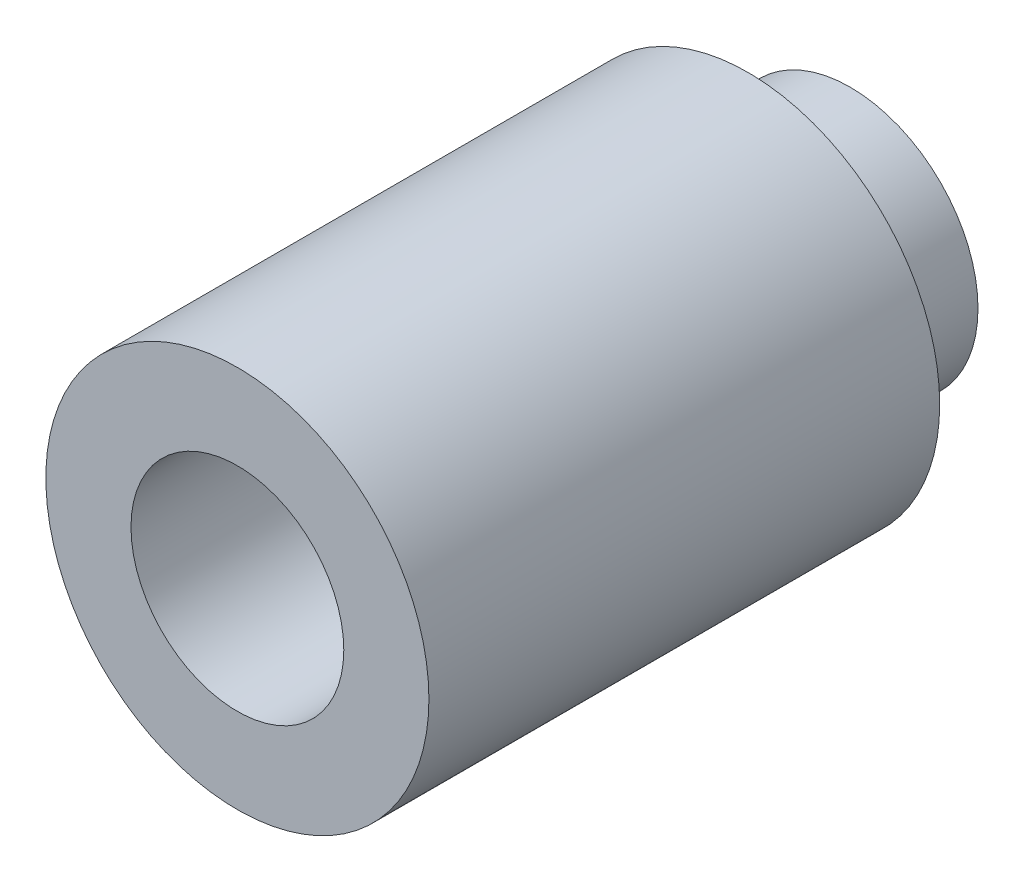
SolidWorks part; units mm, degrees
ref_plane "前视基准面" through (0, 0, 0) normal (0, 0, 1) x (1, 0, 0)
ref_plane "上视基准面" through (0, 0, 0) normal (0, 1, 0) x (1, 0, 0)
ref_plane "右视基准面" through (0, 0, 0) normal (1, 0, 0) x (0, 0, -1)
other "Configuration Table"
sketch "草图1" plane through (0, 0, 0) normal (0, 0, 1) x (1, 0, 0)
  circle A0 centre (0, 0) radius 1.25
  circle A1 centre (0, 0) radius 2.25
  dimension "D1" = 2.5
  dimension "D2" = 4.5
extrude "凸台-拉伸1" add sketch "草图1" along normal blind 6
sketch "草图2" plane through (0, 0, 0) normal (0, 0, -1) x (-1, 0, 0)
  circle A0 centre (0, 0) radius 1.5
  circle A1 centre (0, 0) radius 1.25 construction
  circle A2 centre (0, 0) radius 1.25
  dimension "D1" = 3
extrude "凸台-拉伸2" add sketch "草图2" along normal blind 1.2
